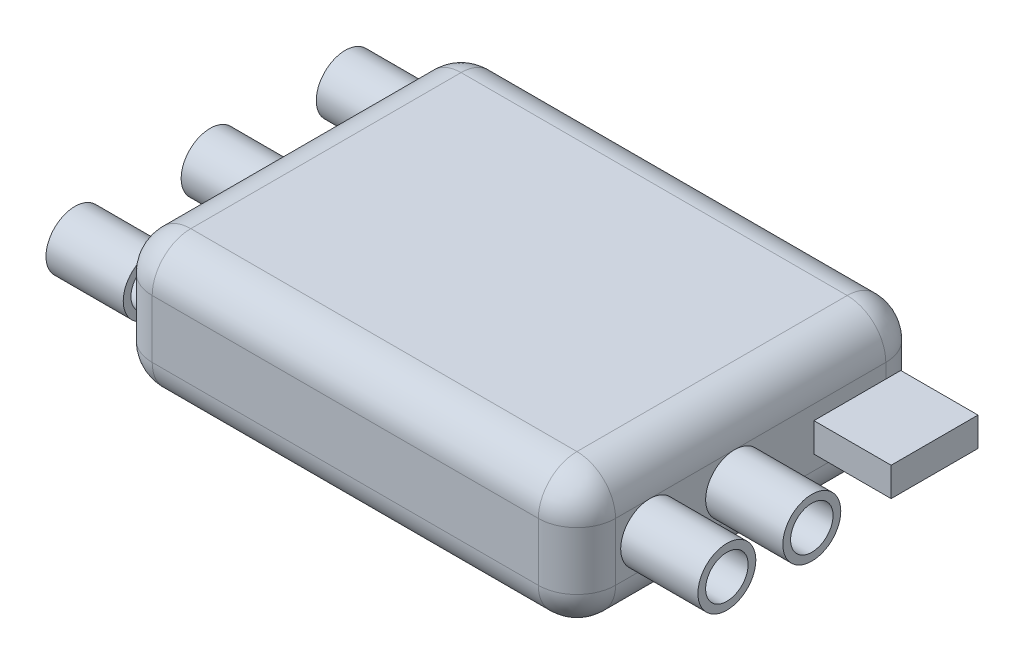
SolidWorks part; units mm, degrees
ref_plane "Front Plane" through (0, 0, 0) normal (0, 0, 1) x (1, 0, 0)
ref_plane "Top Plane" through (0, 0, 0) normal (0, 1, 0) x (1, 0, 0)
ref_plane "Right Plane" through (0, 0, 0) normal (1, 0, 0) x (0, 0, -1)
sketch "Sketch1" plane through (0, 0, 0) normal (0, 1, 0) x (1, 0, 0)
  line L1 (10, 9) -> (-10, 9)
  line L2 (12, 7) -> (12, -7)
  line L3 (10, -9) -> (-10, -9)
  line L4 (-12, 7) -> (-12, -7)
  line L5 (12, 9) -> (-12, -9) construction
  line L6 (12, -9) -> (-12, 9) construction
  arc A0 (-10, -9) -> (-12, -7) centre (-10, -7) cw
  arc A1 (12, -7) -> (10, -9) centre (10, -7) cw
  arc A2 (10, 9) -> (12, 7) centre (10, 7) cw
  arc A3 (-10, 9) -> (-12, 7) centre (-10, 7) ccw
  point P0 (0, 0)
  dimension "D3" = 2
  dimension "D1" = 24
  dimension "D2" = 18
extrude "Boss-Extrude1" add sketch "Sketch1" along normal blind 7
fillet "Fillet1" radius 2 16 edges at (0, 0, 9) (11.4142, 0, 8.4142) (12, 0, 0) (11.4142, 0, -8.4142) (0, 0, -9) (-11.4142, 0, -8.4142) (-12, 0, 0) (-11.4142, 0, 8.4142) (-12, 7, 0) (-11.4142, 7, -8.4142) (0, 7, -9) (11.4142, 7, -8.4142) (12, 7, 0) (11.4142, 7, 8.4142) (0, 7, 9) (-11.4142, 7, 8.4142)
sketch "Sketch2" plane through (-12, 0, 0) normal (-1, 0, 0) x (0, 0, 1)
  line L0 (-7, 3.5) -> (7, 3.5) construction
  line L1 (-7, 5) -> (-7, 2) construction
  line L2 (7, 5) -> (7, 2) construction
  circle A0 centre (0, 3.5) radius 1.5
  circle A1 centre (0, 3.5) radius 1.1
  circle A2 centre (7, 3.5) radius 1.5
  circle A3 centre (7, 3.5) radius 1.1
  circle A4 centre (-7, 3.5) radius 1.5
  circle A5 centre (-7, 3.5) radius 1.1
  dimension "D1" = 3
  dimension "D2" = 0.4
extrude "Boss-Extrude2" add sketch "Sketch2" along normal blind 4
sketch "Sketch3" plane through (12, 0, 0) normal (1, 0, 0) x (0, 0, -1)
  line L0 (-7, 3.5) -> (7, 3.5) construction
  line L1 (-7, 5) -> (-7, 2) construction
  line L2 (7, 5) -> (7, 2) construction
  line L4 (3.2742, 4.25) -> (7.7742, 4.25)
  line L5 (3.2742, 4.25) -> (3.2742, 2.75)
  line L6 (3.2742, 2.75) -> (7.7742, 2.75)
  line L7 (7.7742, 4.25) -> (7.7742, 2.75)
  line L8 (3.2742, 4.25) -> (7.7742, 2.75) construction
  line L9 (3.2742, 2.75) -> (7.7742, 4.25) construction
  circle A0 centre (-5.2334, 3.5) radius 1.5
  circle A1 centre (-5.2334, 3.5) radius 1.1
  circle A2 centre (-0.8334, 3.5) radius 1.5
  circle A3 centre (-0.8334, 3.5) radius 1.1
  point P6 (5.5242, 3.5)
  dimension "D3" = 3
  dimension "D4" = 0.4
  dimension "D1" = 4.5
  dimension "D2" = 1.5
  dimension "D5" = 4.4
extrude "Boss-Extrude3" add sketch "Sketch3" along normal blind 4
